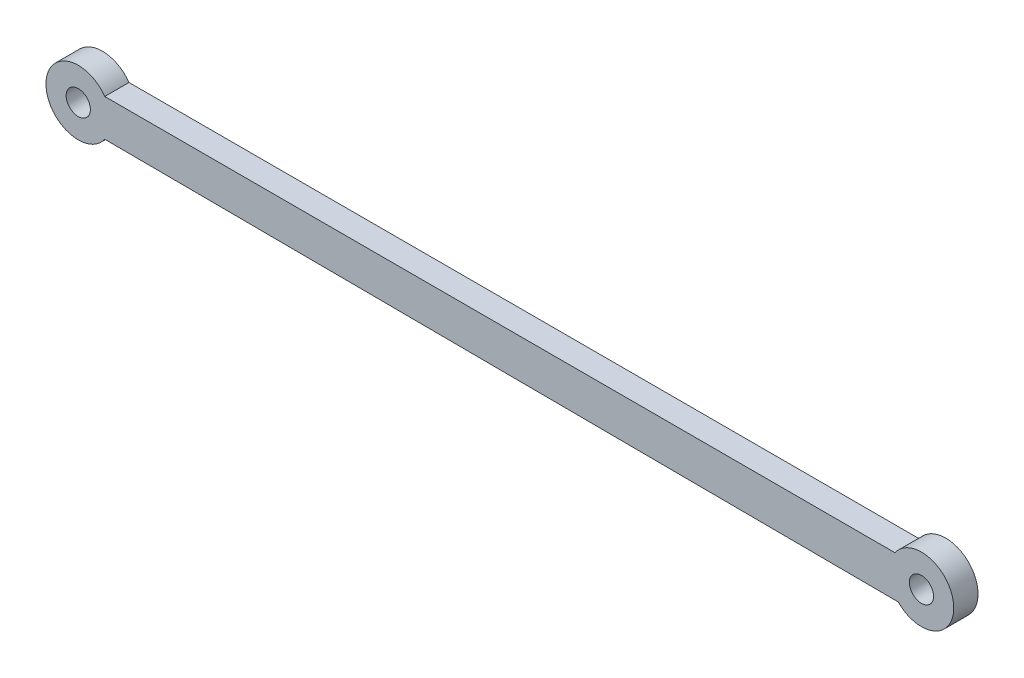
SolidWorks part; units mm, degrees
ref_plane "Front Plane" through (0, 0, 0) normal (0, 0, 1) x (1, 0, 0)
ref_plane "Top Plane" through (0, 0, 0) normal (0, 1, 0) x (1, 0, 0)
ref_plane "Right Plane" through (0, 0, 0) normal (1, 0, 0) x (0, 0, -1)
sketch "Sketch1" plane through (0, 0, 0) normal (0, 0, 1) x (1, 0, 0)
  line L0 (-12.6847, 0) -> (50.0244, 0) construction
  line L1 (3.2776, 2.2929) -> (101.0524, 2.2929)
  line L2 (3.2776, -2.2929) -> (101.4565, -2.7826)
  circle A0 centre (0, 0) radius 1.5
  circle A1 centre (104.33, 0) radius 1.5
  arc A2 (3.2776, 2.2929) -> (3.2776, -2.2929) centre (0, 0) ccw
  arc A3 (101.4565, -2.7826) -> (101.0524, 2.2929) centre (104.33, 0) ccw
  dimension "D1" = 3
  dimension "D2" = 3
  dimension "D4" = 8
  dimension "D5" = 8
  dimension "D3" = 104.33
extrude "Boss-Extrude1" add sketch "Sketch1" along normal blind 3
